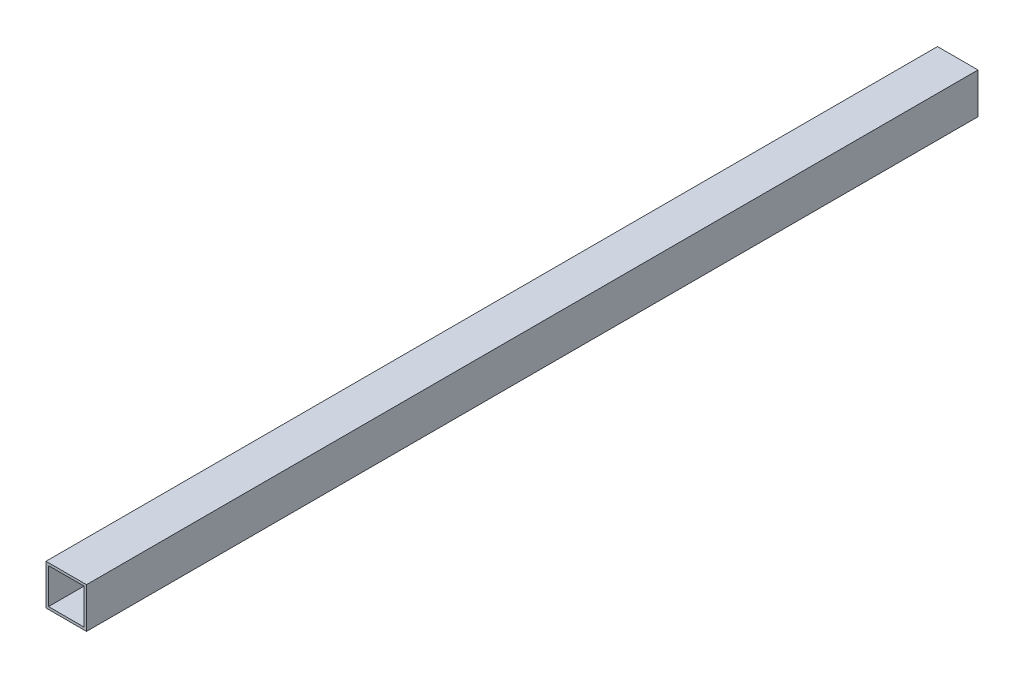
SolidWorks part; units mm, degrees
ref_plane "Front Plane" through (0, 0, 0) normal (0, 0, 1) x (1, 0, 0)
ref_plane "Top Plane" through (0, 0, 0) normal (0, 1, 0) x (1, 0, 0)
ref_plane "Right Plane" through (0, 0, 0) normal (1, 0, 0) x (0, 0, -1)
sketch "Sketch1" plane through (0, 0, 0) normal (0, 0, 1) x (1, 0, 0)
  line L0 (12.7, 0) -> (11.1125, 0) construction
  line L1 (-12.7, 0) -> (12.7, 0) construction
  line L2 (0, 12.7) -> (0, -12.7)
  point P7 (0, 0)
sketch "Sketch2" plane through (0, 0, 0) normal (1, 0, 0) x (0, 0, -1)
  line L0 (914.4, 0) -> (-914.4, 0)
  point P4 (0, 0)
  dimension "Length" = 1828.8
sketch "Sketch3" plane through (0, 0, 0) normal (0, 0, 1) x (1, 0, 0)
  line L5 (-12.7, -12.7) -> (12.7, -12.7)
  line L11 (-12.7, -12.7) -> (-12.7, 12.7)
  line L12 (-12.7, 12.7) -> (12.7, 12.7)
  line L13 (-11.1125, -11.1125) -> (11.1125, -11.1125)
  line L14 (12.7, -12.7) -> (12.7, 12.7)
  line L18 (-12.7, -12.7) -> (12.7, 12.7) construction
  line L19 (-12.7, 12.7) -> (12.7, -12.7) construction
  line L20 (-11.1125, -11.1125) -> (-11.1125, 11.1125)
  line L21 (-11.1125, 11.1125) -> (11.1125, 11.1125)
  line L22 (11.1125, -11.1125) -> (11.1125, 11.1125)
  line L23 (-11.1125, -11.1125) -> (11.1125, 11.1125) construction
  line L24 (-11.1125, 11.1125) -> (11.1125, -11.1125) construction
  point P0 (0, 0)
  point P1 (0, 0)
  point P10 (11.1125, -12.7)
  dimension "D2" = 1.5875
  dimension "D3" = 25.4
  dimension "D4" = 25.4
  dimension "D1" = 1.5875
extrude "Boss-Extrude1" add sketch "Sketch3" along normal up to vertex (914.4 mm away) and the other way up to vertex (914.4 mm away) up to point (0, 0, 914.4) other way up to point (0, 0, -914.4)
sketch "Sketch4" plane through (0, 0, 0) normal (1, 0, 0) x (0, 0, -1)
  line L0 (914.4, 0) -> (-914.4, 0) construction
  line L1 (-914.4, -12.7) -> (-914.4, 12.7) construction
  point P0 (-885.825, 0)
  point P6 (0, 0)
  point P8 (-876.3, 0)
  point P9 (876.3, 0)
  point P10 (885.825, 0)
  dimension "D1" = 28.575
  dimension "D2" = 38.1
  dimension "D3" = 28.575
  dimension "D4" = 38.1
sketch "Sketch5" plane through (0, 0, 914.4) normal (0, 0, 1) x (1, 0, 0)
  line L1 (-36.2582, -31.2976) -> (36.2582, -31.2976)
  line L2 (-36.2582, -31.2976) -> (-36.2582, 31.2976)
  line L3 (-36.2582, 31.2976) -> (36.2582, 31.2976)
  line L4 (36.2582, -31.2976) -> (36.2582, 31.2976)
  line L5 (-36.2582, -31.2976) -> (36.2582, 31.2976) construction
  line L6 (-36.2582, 31.2976) -> (36.2582, -31.2976) construction
  point P0 (0, 0)
extrude "Cut-Extrude1" cut sketch "Sketch5" against normal blind 1270
equation "\"D2@Sketch3\"=\"Wall Thickness@Sketch1\""
equation "\"D1@Sketch4\"=\"Width@Sketch1\"*1.125"
equation "\"D2@Sketch4\"=\"Width@Sketch1\"*1.5"
equation "\"D3@Sketch4\"=\"D1@Sketch4\""
equation "\"D4@Sketch4\"=\"D2@Sketch4\""
